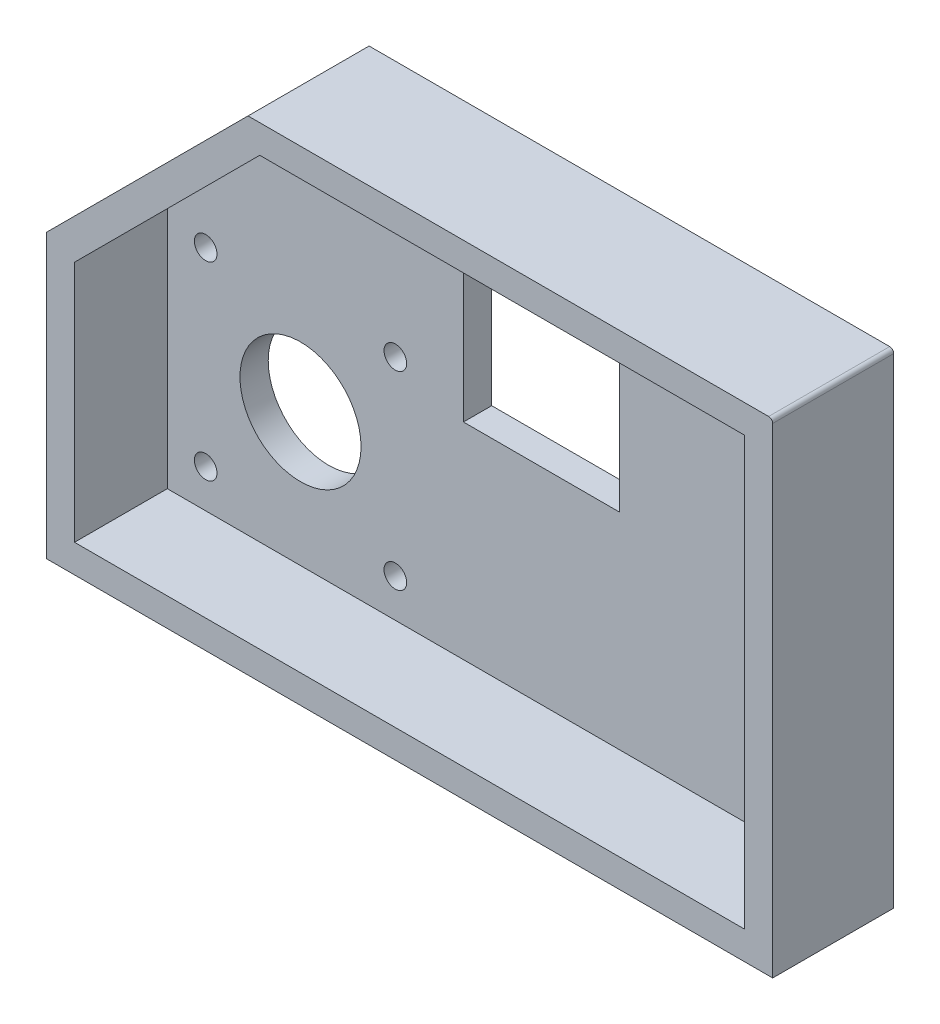
SolidWorks part; units mm, degrees
material "ABS"
ref_plane "Front Plane" through (0, 0, 0) normal (0, 0, 1) x (1, 0, 0)
ref_plane "Top Plane" through (0, 0, 0) normal (0, 1, 0) x (1, 0, 0)
ref_plane "Right Plane" through (0, 0, 0) normal (1, 0, 0) x (0, 0, -1)
sketch "Sketch1" plane through (0, 0, 0) normal (0, 0, 1) x (1, 0, 0)
  line L0 (-48.5799, 70.7779) -> (-98.5799, 20.7779)
  line L1 (-48.5799, 70.7779) -> (80.4201, 70.7779)
  line L2 (-98.5799, 20.7779) -> (-98.5799, -49.2221)
  line L3 (-98.5799, -49.2221) -> (81.4201, -49.2221)
  line L4 (81.4201, 69.7779) -> (81.4201, -49.2221)
  arc A0 (80.4201, 70.7779) -> (81.4201, 69.7779) centre (80.4201, 69.7779) cw
  point P0 (-98.3702, 70.7779)
  point P6 (81.4201, 70.7779)
  point P8 (-98.5799, 70.7779)
  point P9 (-98.5799, 70.7779)
  dimension "D3" = 1
  dimension "D1" = 180
  dimension "D2" = 120
extrude "Boss-Extrude1" add sketch "Sketch1" along normal blind 30
shell "Shell1" thickness 7
sketch "Sketch2" plane through (0, 0, 7) normal (0, 0, 1) x (1, 0, 0)
  line L0 (80.4201, 70.7779) -> (-48.5799, 70.7779) construction
  line L1 (-98.5799, 20.7779) -> (-98.5799, -49.2221) construction
  circle A0 centre (-58.5799, -9.2221) radius 15
  point P4 (0, 0)
  dimension "D1" = 80
  dimension "D2" = 40
extrude "Cut-Extrude1" cut sketch "Sketch2" against normal blind 20
sketch "Sketch3" plane through (0, 0, 7) normal (0, 0, 1) x (1, 0, 0)
  circle A0 centre (-82.0799, 14.2779) radius 2.806
  circle A1 centre (-58.5799, -9.2221) radius 15 construction
  dimension "D1" = 23.5
  dimension "D2" = 23.5
extrude "Cut-Extrude2" cut sketch "Sketch3" against normal blind 20
pattern_linear "LPattern1" count 2 spacing 47 along (1, 0, 0) count 2 spacing 47 along (0, -1, 0) of "Cut-Extrude2"
sketch "Sketch4" plane through (0, 0, 7) normal (0, 0, 1) x (1, 0, 0)
  line L1 (-18.2034, 47.1448) -> (20.4195, 47.1448)
  line L2 (-18.2034, 47.1448) -> (-18.2034, 8.7794)
  line L3 (-18.2034, 8.7794) -> (20.4195, 8.7794)
  line L4 (20.4195, 47.1448) -> (20.4195, 8.7794)
extrude "Cut-Extrude3" cut sketch "Sketch4" against normal blind 20
